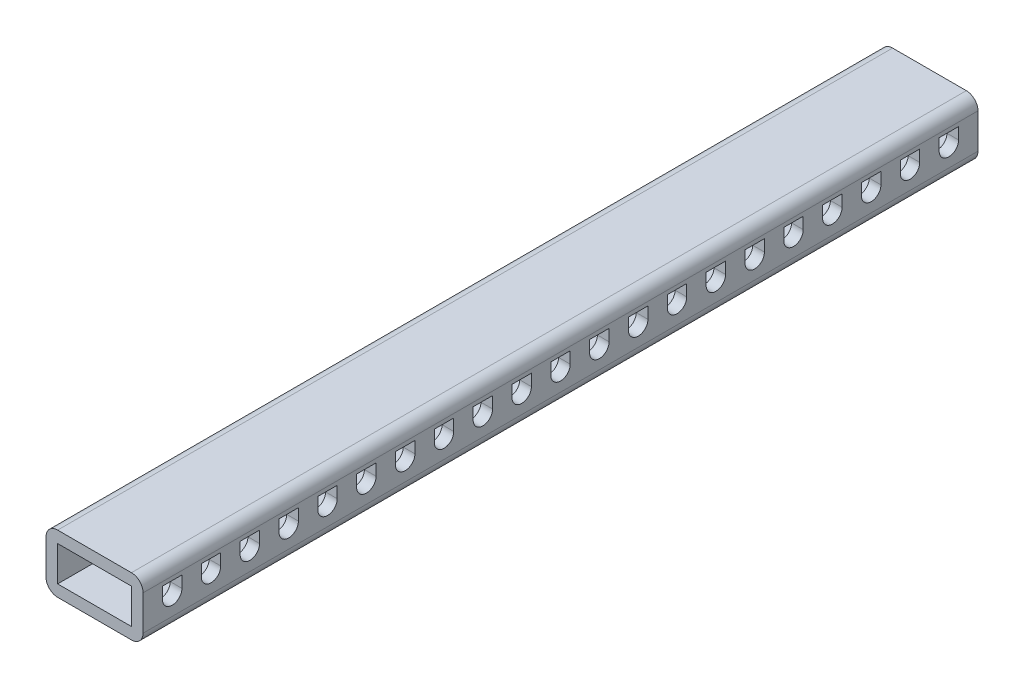
SolidWorks part; units mm, degrees
ref_plane "Front Plane" through (0, 0, 0) normal (0, 0, 1) x (1, 0, 0)
ref_plane "Top Plane" through (0, 0, 0) normal (0, 1, 0) x (1, 0, 0)
ref_plane "Right Plane" through (0, 0, 0) normal (1, 0, 0) x (0, 0, -1)
sketch "Sketch1" plane through (0, 0, 0) normal (0, 0, 1) x (1, 0, 0)
  line L1 (-12.5, 7.5) -> (12.5, 7.5)
  line L2 (-12.5, 7.5) -> (-12.5, -7.5)
  line L3 (-12.5, -7.5) -> (12.5, -7.5)
  line L4 (12.5, 7.5) -> (12.5, -7.5)
  line L5 (-12.5, 7.5) -> (12.5, -7.5) construction
  line L6 (-12.5, -7.5) -> (12.5, 7.5) construction
  point P0 (0, 0)
  dimension "D1" = 25
  dimension "D2" = 15
extrude "Boss-Extrude1" add sketch "Sketch1" along normal blind 215
sketch "Sketch2" plane through (0, 0, 215) normal (0, 0, 1) x (1, 0, 0)
  line L0 (-12.5, 7.5) -> (-12.5, -7.5) construction
  line L1 (-9.5, -4.5) -> (9.5, -4.5)
  line L2 (-9.5, -4.5) -> (-9.5, 4.5)
  line L3 (-9.5, 4.5) -> (9.5, 4.5)
  line L4 (9.5, -4.5) -> (9.5, 4.5)
  line L5 (-9.5, -4.5) -> (9.5, 4.5) construction
  line L6 (-9.5, 4.5) -> (9.5, -4.5) construction
  line L7 (12.5, 7.5) -> (-12.5, 7.5) construction
  point P0 (0, 0)
  dimension "D1" = 3
  dimension "D2" = 3
extrude "Cut-Extrude1" cut sketch "Sketch2" against normal blind 263
sketch "Sketch3" plane through (12.5, 0, 0) normal (1, 0, 0) x (0, 0, -1)
  line L1 (-215, 7.5) -> (0, 7.5) construction
  line L2 (-210, 3.5) -> (-205, 3.5)
  line L3 (-210, 3.5) -> (-210, 0.5)
  line L5 (-205, 3.5) -> (-205, 0.5)
  line L6 (-215, -7.5) -> (-215, 7.5) construction
  line L7 (-202.5, 7.5) -> (-202.5, 3.8883) construction
  line L8 (-200, 3.5) -> (-200, 0.5)
  line L9 (-195, 3.5) -> (-195, 0.5)
  line L10 (-195, 3.5) -> (-200, 3.5)
  line L11 (-192.5, 7.5) -> (-192.5, 3.8883) construction
  line L12 (-182.5, 7.5) -> (-182.5, 3.8883) construction
  line L13 (-190, 3.5) -> (-185, 3.5)
  line L14 (-190, 3.5) -> (-190, 0.5)
  line L15 (-185, 3.5) -> (-185, 0.5)
  line L16 (-180, 3.5) -> (-180, 0.5)
  line L17 (-175, 3.5) -> (-175, 0.5)
  line L18 (-175, 3.5) -> (-180, 3.5)
  line L19 (-172.5, 7.5) -> (-172.5, 3.8883) construction
  line L20 (-162.5, 7.5) -> (-162.5, 3.8883) construction
  line L21 (-180, 3.5) -> (-180, 0.5)
  line L22 (-175, 3.5) -> (-175, 0.5)
  line L23 (-175, 3.5) -> (-180, 3.5)
  line L24 (-170, 3.5) -> (-165, 3.5)
  line L25 (-170, 3.5) -> (-170, 0.5)
  line L26 (-165, 3.5) -> (-165, 0.5)
  line L27 (-160, 3.5) -> (-160, 0.5)
  line L28 (-155, 3.5) -> (-155, 0.5)
  line L29 (-155, 3.5) -> (-160, 3.5)
  line L30 (-152.5, 7.5) -> (-152.5, 3.8883) construction
  line L31 (-142.5, 7.5) -> (-142.5, 3.8883) construction
  line L32 (-132.5, 7.5) -> (-132.5, 3.8883) construction
  line L33 (-122.5, 7.5) -> (-122.5, 3.8883) construction
  line L34 (-160, 3.5) -> (-160, 0.5)
  line L35 (-155, 3.5) -> (-155, 0.5)
  line L36 (-155, 3.5) -> (-160, 3.5)
  line L37 (-150, 3.5) -> (-145, 3.5)
  line L38 (-150, 3.5) -> (-150, 0.5)
  line L39 (-145, 3.5) -> (-145, 0.5)
  line L40 (-150, 3.5) -> (-145, 3.5)
  line L41 (-150, 3.5) -> (-150, 0.5)
  line L42 (-145, 3.5) -> (-145, 0.5)
  line L43 (-140, 3.5) -> (-140, 0.5)
  line L44 (-135, 3.5) -> (-135, 0.5)
  line L45 (-135, 3.5) -> (-140, 3.5)
  line L46 (-130, 3.5) -> (-125, 3.5)
  line L47 (-130, 3.5) -> (-130, 0.5)
  line L48 (-125, 3.5) -> (-125, 0.5)
  line L49 (-120, 3.5) -> (-120, 0.5)
  line L50 (-115, 3.5) -> (-115, 0.5)
  line L51 (-115, 3.5) -> (-120, 3.5)
  line L52 (-112.5, 7.5) -> (-112.5, 3.8883) construction
  line L53 (-102.5, 7.5) -> (-102.5, 3.8883) construction
  line L54 (-92.5, 7.5) -> (-92.5, 3.8883) construction
  line L55 (-82.5, 7.5) -> (-82.5, 3.8883) construction
  line L56 (-72.5, 7.5) -> (-72.5, 3.8883) construction
  line L57 (-62.5, 7.5) -> (-62.5, 3.8883) construction
  line L58 (-52.5, 7.5) -> (-52.5, 3.8883) construction
  line L59 (-42.5, 7.5) -> (-42.5, 3.8883) construction
  line L60 (-120, 3.5) -> (-120, 0.5)
  line L61 (-115, 3.5) -> (-115, 0.5)
  line L62 (-115, 3.5) -> (-120, 3.5)
  line L63 (-110, 3.5) -> (-105, 3.5)
  line L64 (-110, 3.5) -> (-110, 0.5)
  line L65 (-105, 3.5) -> (-105, 0.5)
  line L66 (-100, 3.5) -> (-100, 0.5)
  line L67 (-95, 3.5) -> (-95, 0.5)
  line L68 (-95, 3.5) -> (-100, 3.5)
  line L69 (-100, 3.5) -> (-100, 0.5)
  line L70 (-95, 3.5) -> (-95, 0.5)
  line L71 (-95, 3.5) -> (-100, 3.5)
  line L72 (-90, 3.5) -> (-85, 3.5)
  line L73 (-90, 3.5) -> (-90, 0.5)
  line L74 (-85, 3.5) -> (-85, 0.5)
  line L75 (-90, 3.5) -> (-85, 3.5)
  line L76 (-90, 3.5) -> (-90, 0.5)
  line L77 (-85, 3.5) -> (-85, 0.5)
  line L78 (-80, 3.5) -> (-80, 0.5)
  line L79 (-75, 3.5) -> (-75, 0.5)
  line L80 (-75, 3.5) -> (-80, 3.5)
  line L81 (-70, 3.5) -> (-65, 3.5)
  line L82 (-70, 3.5) -> (-70, 0.5)
  line L83 (-65, 3.5) -> (-65, 0.5)
  line L84 (-70, 3.5) -> (-65, 3.5)
  line L85 (-70, 3.5) -> (-70, 0.5)
  line L86 (-65, 3.5) -> (-65, 0.5)
  line L87 (-60, 3.5) -> (-60, 0.5)
  line L88 (-55, 3.5) -> (-55, 0.5)
  line L89 (-55, 3.5) -> (-60, 3.5)
  line L90 (-50, 3.5) -> (-45, 3.5)
  line L91 (-50, 3.5) -> (-50, 0.5)
  line L92 (-45, 3.5) -> (-45, 0.5)
  line L93 (-40, 3.5) -> (-40, 0.5)
  line L94 (-35, 3.5) -> (-35, 0.5)
  line L95 (-35, 3.5) -> (-40, 3.5)
  line L96 (-40, 3.5) -> (-40, 0.5)
  line L97 (-10, 3.5) -> (-5, 3.5)
  line L98 (-10, 3.5) -> (-10, 0.5)
  line L99 (-5, 3.5) -> (-5, 0.5)
  line L100 (-32.5, 7.5) -> (-32.5, 3.8883) construction
  line L101 (-22.5, 7.5) -> (-22.5, 3.8883) construction
  line L102 (-12.5, 7.5) -> (-12.5, 3.8883) construction
  line L103 (-35, 3.5) -> (-35, 0.5)
  line L104 (-35, 3.5) -> (-40, 3.5)
  line L105 (-30, 3.5) -> (-25, 3.5)
  line L106 (-30, 3.5) -> (-30, 0.5)
  line L107 (-25, 3.5) -> (-25, 0.5)
  line L108 (-20, 3.5) -> (-20, 0.5)
  line L109 (-15, 3.5) -> (-15, 0.5)
  line L110 (-15, 3.5) -> (-20, 3.5)
  line L111 (-20, 3.5) -> (-20, 0.5)
  line L112 (-15, 3.5) -> (-15, 0.5)
  line L113 (-15, 3.5) -> (-20, 3.5)
  line L114 (-2.5, 7.5) -> (-2.5, 3.8883) construction
  line L115 (-10, 3.5) -> (-5, 3.5)
  line L116 (-10, 3.5) -> (-10, 0.5)
  line L117 (-5, 3.5) -> (-5, 0.5)
  line L118 (-10, 3.5) -> (-5, 3.5)
  line L119 (-10, 3.5) -> (-10, 0.5)
  line L120 (-5, 3.5) -> (-5, 0.5)
  line L121 (0, 3.5) -> (0, 0.5)
  line L122 (5, 3.5) -> (5, 0.5)
  line L123 (5, 3.5) -> (0, 3.5)
  arc A0 (-210, 0.5) -> (-205, 0.5) centre (-207.5, 0.5) ccw
  arc A1 (-195, 0.5) -> (-200, 0.5) centre (-197.5, 0.5) cw
  arc A2 (-190, 0.5) -> (-185, 0.5) centre (-187.5, 0.5) ccw
  arc A3 (-175, 0.5) -> (-180, 0.5) centre (-177.5, 0.5) cw
  arc A4 (-175, 0.5) -> (-180, 0.5) centre (-177.5, 0.5) cw
  arc A5 (-170, 0.5) -> (-165, 0.5) centre (-167.5, 0.5) ccw
  arc A6 (-155, 0.5) -> (-160, 0.5) centre (-157.5, 0.5) cw
  arc A7 (-155, 0.5) -> (-160, 0.5) centre (-157.5, 0.5) cw
  arc A8 (-150, 0.5) -> (-145, 0.5) centre (-147.5, 0.5) ccw
  arc A9 (-150, 0.5) -> (-145, 0.5) centre (-147.5, 0.5) ccw
  arc A10 (-135, 0.5) -> (-140, 0.5) centre (-137.5, 0.5) cw
  arc A11 (-130, 0.5) -> (-125, 0.5) centre (-127.5, 0.5) ccw
  arc A12 (-115, 0.5) -> (-120, 0.5) centre (-117.5, 0.5) cw
  arc A13 (-115, 0.5) -> (-120, 0.5) centre (-117.5, 0.5) cw
  arc A14 (-110, 0.5) -> (-105, 0.5) centre (-107.5, 0.5) ccw
  arc A15 (-95, 0.5) -> (-100, 0.5) centre (-97.5, 0.5) cw
  arc A16 (-95, 0.5) -> (-100, 0.5) centre (-97.5, 0.5) cw
  arc A17 (-90, 0.5) -> (-85, 0.5) centre (-87.5, 0.5) ccw
  arc A18 (-90, 0.5) -> (-85, 0.5) centre (-87.5, 0.5) ccw
  arc A19 (-75, 0.5) -> (-80, 0.5) centre (-77.5, 0.5) cw
  arc A20 (-70, 0.5) -> (-65, 0.5) centre (-67.5, 0.5) ccw
  arc A21 (-70, 0.5) -> (-65, 0.5) centre (-67.5, 0.5) ccw
  arc A22 (-55, 0.5) -> (-60, 0.5) centre (-57.5, 0.5) cw
  arc A23 (-50, 0.5) -> (-45, 0.5) centre (-47.5, 0.5) ccw
  arc A24 (-35, 0.5) -> (-40, 0.5) centre (-37.5, 0.5) cw
  arc A25 (-10, 0.5) -> (-5, 0.5) centre (-7.5, 0.5) ccw
  arc A26 (-35, 0.5) -> (-40, 0.5) centre (-37.5, 0.5) cw
  arc A27 (-30, 0.5) -> (-25, 0.5) centre (-27.5, 0.5) ccw
  arc A28 (-15, 0.5) -> (-20, 0.5) centre (-17.5, 0.5) cw
  arc A29 (-15, 0.5) -> (-20, 0.5) centre (-17.5, 0.5) cw
  arc A30 (-10, 0.5) -> (-5, 0.5) centre (-7.5, 0.5) ccw
  arc A31 (-10, 0.5) -> (-5, 0.5) centre (-7.5, 0.5) ccw
  arc A32 (5, 0.5) -> (0, 0.5) centre (2.5, 0.5) cw
  point P18 (-195, 2)
  dimension "D1" = 4
  dimension "D2" = 5
  dimension "D3" = 5
  dimension "D4" = 3
  dimension "D5" = 5
  dimension "D6" = 5
extrude "Cut-Extrude2" cut sketch "Sketch3" against normal blind 263 contours L3 A0 L5 L2 | A1 L9 L10 L8 | L14 A2 L15 L13 | A3 L17 L18 L16 | L25 A5 L26 L24 | A6 L28 L29 L27 | L38 A8 L39 L37 | A10 L44 L45 L43 | L47 A11 L48 L46 | A12 L50 L51 L49 | L64 A14 L65 L63 | A15 L67 L68 L66 | L73 A17 L74 L72 | A19 L79 L80 L78 | L82 A20 L83 L81 | A22 L88 L89 L87 | L91 A23 L92 L90 | A24 L94 L95 L93 | L106 A27 L107 L105 | A28 L109 L110 L108 | L98 A25 L99 L97 | A32 L122 L123 L121
fillet "Fillet1" radius 3 4 edges at (-12.5, -7.5, 107.5) (12.5, -7.5, 107.5) (12.5, 7.5, 107.5) (-12.5, 7.5, 107.5)
